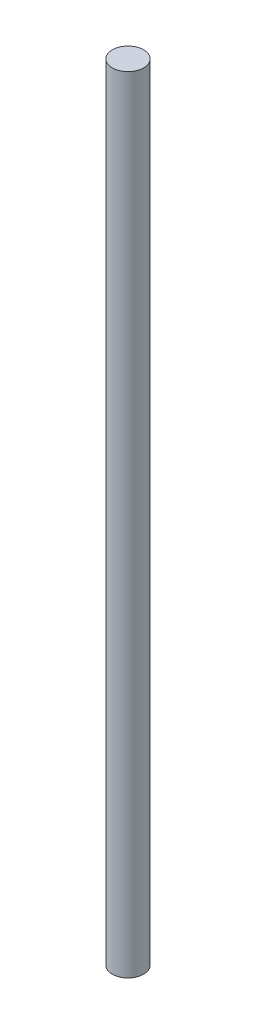
SolidWorks part; units mm, degrees
ref_plane "Front Plane" through (0, 0, 0) normal (0, 0, 1) x (1, 0, 0)
ref_plane "Top Plane" through (0, 0, 0) normal (0, 1, 0) x (1, 0, 0)
ref_plane "Right Plane" through (0, 0, 0) normal (1, 0, 0) x (0, 0, -1)
sketch "Sketch1" plane through (0, 0, 0) normal (0, 1, 0) x (1, 0, 0)
  circle A0 centre (0, 0) radius 3
extrude "Boss-Extrude1" add sketch "Sketch1" along normal blind 150
